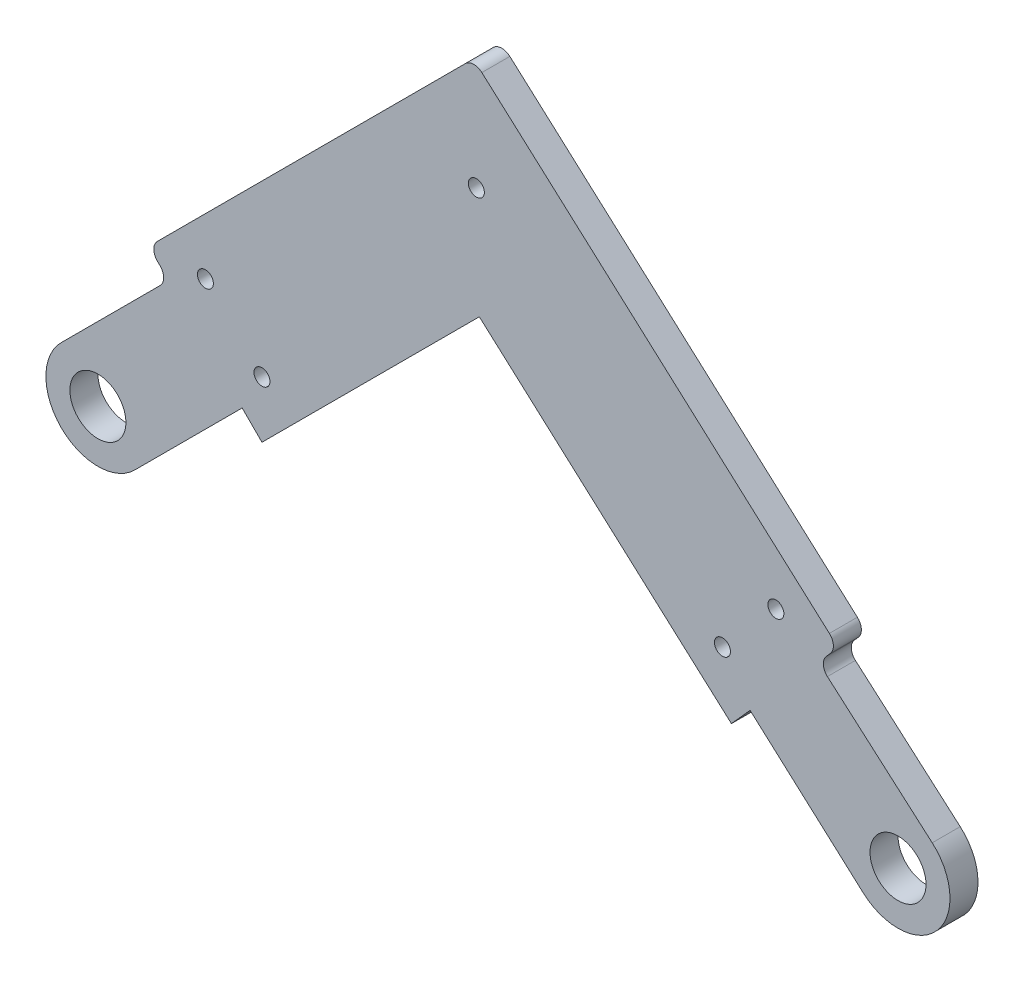
SolidWorks part; units mm, degrees
ref_plane "Front Plane" through (0, 0, 0) normal (0, 0, 1) x (1, 0, 0)
ref_plane "Top Plane" through (0, 0, 0) normal (0, 1, 0) x (1, 0, 0)
ref_plane "Right Plane" through (0, 0, 0) normal (1, 0, 0) x (0, 0, -1)
sketch "Sketch2" plane through (0, 0, 0) normal (0, 0, 1) x (1, 0, 0)
  line L0 (-100, 0) -> (100, 0) construction
  line L1 (-100, 0) -> (0, 100) construction
  line L2 (0, 100) -> (100, 0) construction
  line L3 (0, 0) -> (-52.6991, 47.3009) construction
  line L4 (-40, 60) -> (40, 60) construction
  line L5 (0, 100) -> (0, 60) construction
  circle A0 centre (-100, 0) radius 20
  circle A1 centre (0, 0) radius 20
  circle A2 centre (100, 0) radius 20
  point P2 (0, 0)
  dimension "D5" = 40
  dimension "D1" = 200
  dimension "D2" = 93.09
  dimension "D3" = 80
  dimension "D4" = 90
sketch "Sketch3" plane through (0, 0, 0) normal (0, 0, 1) x (1, 0, 0)
  line L0 (-40, 60) -> (-56.5165, 43.4835) construction
  line L1 (75.9584, 9.8995) -> (90.1005, 24.0416) construction
  line L2 (-40, 60) -> (40, 60) construction
  line L3 (40, 60) -> (86.565, 13.435) construction
  line L4 (0, 100) -> (100, 0) construction
  line L5 (86.565, 13.435) -> (40, 60) construction
  line L6 (-100, 0) -> (0, 100) construction
  line L7 (44.1421, 70) -> (93.636, 20.5061)
  line L8 (-44.1421, 70) -> (44.1421, 70)
  line L9 (-44.1421, 70) -> (-63.5876, 50.5546)
  line L10 (35.8579, 50) -> (79.4939, 6.364)
  line L11 (-35.8579, 50) -> (35.8579, 50)
  line L12 (-35.8579, 50) -> (-49.4454, 36.4124)
  line L13 (-63.5876, 50.5546) -> (-49.4454, 36.4124)
  line L14 (79.4939, 6.364) -> (93.636, 20.5061)
  line L15 (81.9688, 8.8388) -> (95.4038, -4.5962)
  line L16 (90.9809, 17.8509) -> (104.534, 4.6576)
  line L17 (-3.4304, 82.6944) -> (-6, 70)
  line L18 (0, 100) -> (0, 60) construction
  line L19 (3.4304, 82.6944) -> (6, 70)
  circle A0 centre (100, 0) radius 3.5
  circle A1 centre (100, 0) radius 10 construction
  arc A2 (95.4038, -4.5962) -> (104.534, 4.6576) centre (100, 0) ccw
  circle A3 centre (100, 0) radius 0.5
  circle A4 centre (100, 0) radius 20 construction
  circle A5 centre (100, 0) radius 6.5 construction
  circle A6 centre (79.4939, 13.435) radius 1
  circle A7 centre (86.565, 20.5061) radius 1
  circle A8 centre (0, 60) radius 1.5
  circle A11 centre (0, 82) radius 1.5
  arc A12 (3.4304, 82.6944) -> (-3.4304, 82.6944) centre (0, 82) ccw
  circle A13 centre (0, 82) radius 3.5 construction
  circle A14 centre (-52.6991, 47.3009) radius 1
  dimension "D4" = 20
  dimension "D5" = 7
  dimension "D10" = 2
  dimension "D11" = 3
  dimension "D15" = 2
  dimension "D3" = 27.5
  dimension "D8" = 19
  dimension "D9" = 5
  dimension "D12" = 2
  dimension "D14" = 6
  dimension "D13" = 6
  dimension "D16" = 5
  dimension "D17" = 5
  dimension "D18" = 12
  dimension "D1" = 10
  dimension "D2" = 10
  dimension "D6" = 3
  dimension "D7" = 3
sketch "Sketch4" plane through (0, 0, 0) normal (0, 0, 1) x (1, 0, 0)
  line L0 (-100, 0) -> (100, 0) construction
  line L1 (-88.5703, 11.4297) -> (-52.6991, 47.3009) construction
  line L2 (-100, 0) -> (0, 100) construction
  line L3 (-52.6991, 47.3009) -> (-14.1397, 12.6913) construction
  line L4 (0, 0) -> (-52.6991, 47.3009) construction
  line L5 (-79.4939, 6.364) -> (-52.3277, 33.5302)
  line L6 (-52.3277, 33.5302) -> (-20.8193, 5.2493)
  line L7 (-93.636, 20.5061) -> (-53.0706, 61.0716)
  line L8 (-53.0706, 61.0716) -> (-7.4601, 20.1332)
  line L9 (-95.6414, 18.5007) -> (-53.0706, 61.0716) construction
  line L10 (-81.4993, 4.3586) -> (-52.3277, 33.5302) construction
  line L11 (-7.4601, 20.1332) -> (-20.8193, 5.2493)
  line L13 (-79.4939, 6.364) -> (-93.636, 20.5061)
  line L14 (-91.1612, 18.0312) -> (-104.5962, 4.5962)
  line L15 (-81.9688, 8.8388) -> (-95.4038, -4.5962)
  line L16 (-9.9683, 17.3388) -> (4.2763, 4.8952)
  line L17 (-18.4815, 7.854) -> (-4.3418, -4.8373)
  line L18 (9.9995, -0.1043) -> (10.0659, -0.1623)
  line L19 (-90.1005, 24.0416) -> (-75.9584, 9.8995) construction
  line L20 (-25.2845, 9.2571) -> (-11.9252, 24.141) construction
  circle A0 centre (-100, 0) radius 10 construction
  circle A1 centre (0, 0) radius 10 construction
  circle A6 centre (-100, 0) radius 3.5
  circle A7 centre (0, 0) radius 3.5
  arc A8 (-104.5962, 4.5962) -> (-95.4038, -4.5962) centre (-100, 0) ccw
  arc A9 (-4.3418, -4.8373) -> (4.2763, 4.8952) centre (0, 0) ccw
  circle A10 centre (0, 0) radius 20 construction
  circle A11 centre (0, 0) radius 6.5 construction
  circle A12 centre (-100, 0) radius 6.5 construction
  circle A13 centre (-86.565, 20.5061) radius 1
  circle A14 centre (-79.4939, 13.435) radius 1
  circle A15 centre (-21.9447, 12.9781) radius 1
  circle A16 centre (-15.2651, 20.42) radius 1
  dimension "D1" = 20
  dimension "D2" = 7
  dimension "D10" = 5
  dimension "D13" = 2
  dimension "D7" = 19
  dimension "D8" = 19
  dimension "D9" = 5
  dimension "D11" = 5
  dimension "D12" = 5
  dimension "D14" = 6
  dimension "D15" = 5
  dimension "D3" = 3
  dimension "D4" = 3
  dimension "D5" = 10
  dimension "D6" = 10
sketch "Sketch5" plane through (0, 0, 0) normal (0, 0, 1) x (1, 0, 0)
  line L13 (-44.1421, 70) -> (44.1421, 70)
  line L14 (44.1421, 70) -> (57.8914, 80.5)
  line L16 (57.8914, 80.5) -> (57.8914, 90.5)
  line L17 (57.8914, 90.5) -> (-57.1086, 90.5)
  line L18 (-57.1086, 90.5) -> (-57.1086, 80.5)
  line L19 (-57.1086, 80.5) -> (-44.1421, 70)
  line L20 (-4, 60) -> (-4, 70)
  line L21 (4, 60) -> (4, 70)
  line L22 (-22.5, 82) -> (22.5, 82) construction
  line L23 (0, 100) -> (0, 60) construction
  line L24 (-22.5, 86.5) -> (22.5, 86.5)
  line L25 (-22.5, 77.5) -> (22.5, 77.5)
  circle A0 centre (0, 60) radius 1.5 construction
  circle A1 centre (0, 60) radius 1.5
  arc A2 (-4, 60) -> (4, 60) centre (0, 60) ccw
  circle A3 centre (0, 60) radius 4 construction
  arc A4 (-22.5, 86.5) -> (-22.5, 77.5) centre (-22.5, 82) ccw
  arc A5 (22.5, 77.5) -> (22.5, 86.5) centre (22.5, 82) ccw
  point P21 (0, 82)
  dimension "D1" = 115
  dimension "D2" = 10
  dimension "D3" = 2.5
  dimension "D4" = 45
  dimension "D5" = 9
  dimension "D6" = 4
  dimension "D7" = 141
sketch "Sketch6" plane through (0, 0, 0) normal (0, 0, 1) x (1, 0, 0)
  line L0 (-81.9688, 8.8388) -> (-95.4038, -4.5962) construction
  line L1 (-91.1612, 18.0312) -> (-104.5962, 4.5962) construction
  line L2 (9.9995, -0.1043) -> (10.0659, -0.1623) construction
  line L3 (-9.9683, 17.3388) -> (4.2763, 4.8952) construction
  line L4 (-18.4815, 7.854) -> (-4.3418, -4.8373) construction
  line L5 (-81.9688, 8.8388) -> (-95.4038, -4.5962)
  line L6 (-79.4939, 6.364) -> (-52.3277, 33.5302)
  line L7 (-52.3277, 33.5302) -> (-20.8193, 5.2493)
  line L8 (-20.8193, 5.2493) -> (-7.4601, 20.1332)
  line L9 (-7.4601, 20.1332) -> (-53.0706, 61.0716)
  line L10 (-53.0706, 61.0716) -> (-93.636, 20.5061)
  line L11 (-93.636, 20.5061) -> (-79.4939, 6.364)
  line L12 (-79.4939, 6.364) -> (-52.3277, 33.5302)
  line L13 (-52.3277, 33.5302) -> (-20.8193, 5.2493)
  line L14 (-20.8193, 5.2493) -> (-18.4815, 7.854)
  line L15 (-7.4601, 20.1332) -> (-53.0706, 61.0716)
  line L16 (-53.0706, 61.0716) -> (-93.636, 20.5061)
  line L17 (-93.636, 20.5061) -> (-91.1612, 18.0312)
  line L18 (-91.1612, 18.0312) -> (-104.5962, 4.5962)
  line L19 (9.9995, -0.1043) -> (10.0659, -0.1623)
  line L20 (-9.9683, 17.3388) -> (4.2763, 4.8952)
  line L21 (-18.4815, 7.854) -> (-4.3418, -4.8373)
  line L22 (-81.9688, 8.8388) -> (-79.4939, 6.364)
  line L23 (-9.9683, 17.3388) -> (-7.4601, 20.1332)
  arc A0 (-104.5962, 4.5962) -> (-95.4038, -4.5962) centre (-100, 0) ccw construction
  circle A1 centre (0, 0) radius 3.5
  circle A2 centre (0, 0) radius 3.5
  circle A3 centre (-100, 0) radius 3.5
  circle A4 centre (-100, 0) radius 3.5
  circle A5 centre (-86.565, 20.5061) radius 1
  circle A6 centre (-86.565, 20.5061) radius 1
  circle A7 centre (-15.2651, 20.42) radius 1
  circle A8 centre (-15.2651, 20.42) radius 1
  circle A9 centre (-21.9447, 12.9781) radius 1
  circle A10 centre (-21.9447, 12.9781) radius 1
  circle A11 centre (-79.4939, 13.435) radius 1
  circle A12 centre (-79.4939, 13.435) radius 1
  arc A13 (-4.3418, -4.8373) -> (4.2763, 4.8952) centre (0, 0) ccw construction
  arc A14 (-104.5962, 4.5962) -> (-95.4038, -4.5962) centre (-100, 0) ccw
  arc A15 (-4.3418, -4.8373) -> (4.2763, 4.8952) centre (0, 0) ccw
  circle A16 centre (-52.6991, 47.3009) radius 1
  dimension "D8" = 2
  dimension "D1" = 0
  dimension "D2" = 0
  dimension "D3" = 0
  dimension "D4" = 0
  dimension "D5" = 0
  dimension "D6" = 0
  dimension "D7" = 0
extrude "Boss-Extrude2" add sketch "Sketch6" along normal blind 3.5 contours L21 A15 L20 L23 L15 L16 L17 L18 A14 L5 L22 L12 L13 L14 A16 A2 A4 A6 A8 A10 A12
fillet "Fillet1" radius 1.5 5 edges at (-91.1612, 18.0312, 1.75) (-93.636, 20.5061, 1.75) (-9.9683, 17.3388, 1.75) (-7.4601, 20.1332, 1.75) (-53.0706, 61.0716, 1.75)
